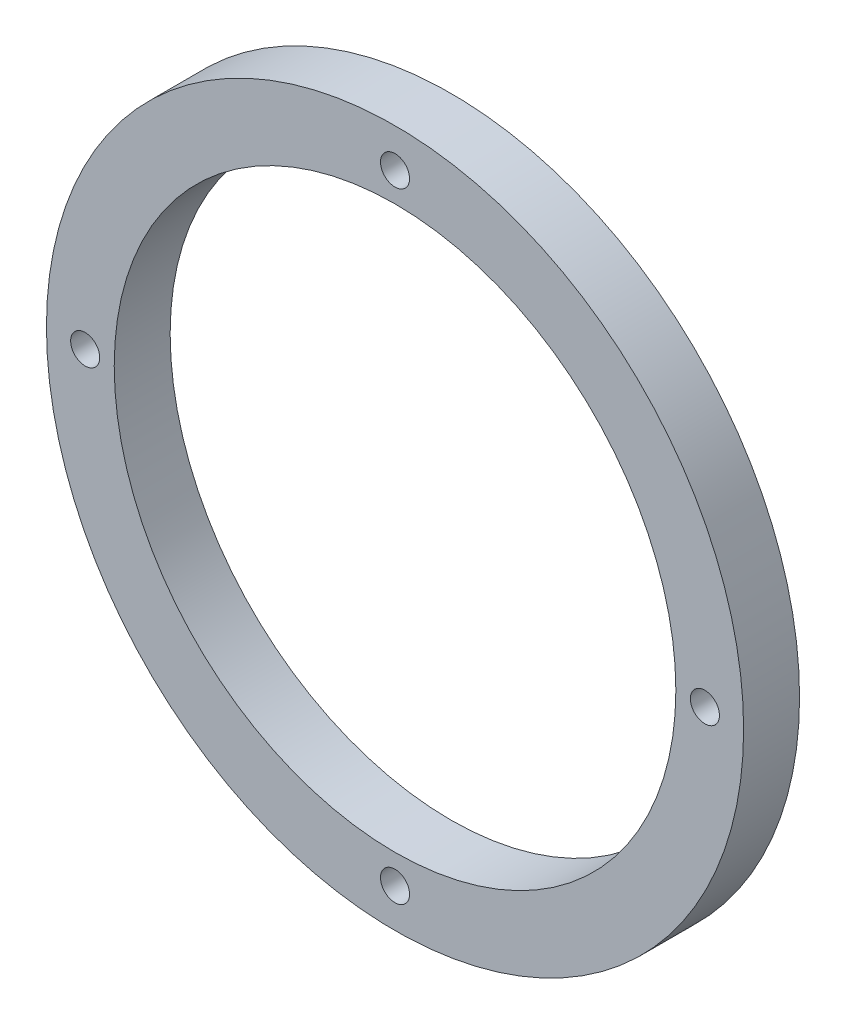
SolidWorks part; units mm, degrees
ref_plane "Front Plane" through (0, 0, 0) normal (0, 0, 1) x (1, 0, 0)
ref_plane "Top Plane" through (0, 0, 0) normal (0, 1, 0) x (1, 0, 0)
ref_plane "Right Plane" through (0, 0, 0) normal (1, 0, 0) x (0, 0, -1)
sketch "Sketch1" plane through (0, 0, 0) normal (0, 0, 1) x (1, 0, 0)
  line L0 (0, 50.8) -> (0, 0) construction
  line L1 (-50.8, 0) -> (0, 0) construction
  circle A0 centre (0, 0) radius 57.15
  circle A1 centre (0, 0) radius 46.0375
  circle A2 centre (0, 50.8) radius 2.3812
  circle A3 centre (50.8, 0) radius 2.3812
  circle A4 centre (0, -50.8) radius 2.3813
  circle A5 centre (-50.8, 0) radius 2.3812
  point P16 (0, 0)
  dimension "D1" = 114.3
  dimension "D3" = 4.7625
  dimension "D4" = 50.8
  dimension "D6" = 50.8
  dimension "D2" = 11.1125
  dimension "D5" = 4
extrude "Boss-Extrude1" add sketch "Sketch1" along normal blind 9.1694
